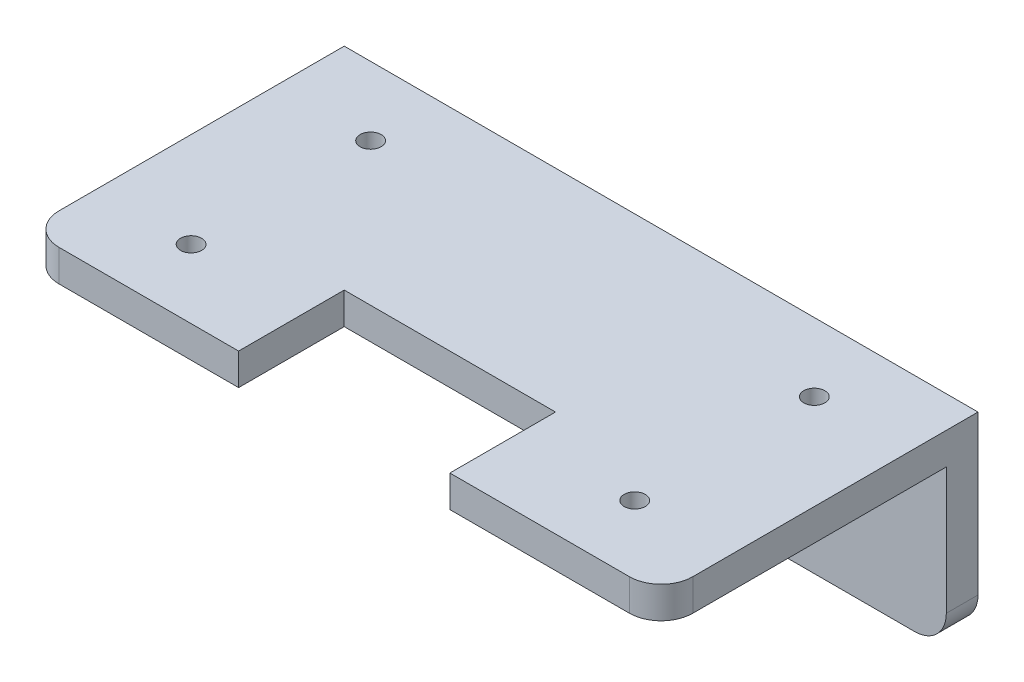
SolidWorks part; units mm, degrees
ref_plane "Front Plane" through (0, 0, 0) normal (0, 0, 1) x (1, 0, 0)
ref_plane "Top Plane" through (0, 0, 0) normal (0, 1, 0) x (1, 0, 0)
ref_plane "Right Plane" through (0, 0, 0) normal (1, 0, 0) x (0, 0, -1)
sketch "Sketch1" plane through (0, 0, 0) normal (0, 0, 1) x (1, 0, 0)
  line L0 (80, 160) -> (-80, 160) construction
  line L1 (-30, 160) -> (30, 160)
  line L2 (-30, 160) -> (-30, 157)
  line L3 (-30, 157) -> (30, 157)
  line L4 (30, 160) -> (30, 157)
  line L5 (0, 164) -> (0, 138.3232) construction
  line L6 (-4.5, 164) -> (4.5, 164) construction
  dimension "D1" = 30
  dimension "D2" = 60
  dimension "D3" = 3
extrude "Boss-Extrude1" add sketch "Sketch1" along normal blind 30
sketch "Sketch2" plane through (0, 157, 0) normal (0, -1, 0) x (1, 0, 0)
  line L0 (30, 30) -> (30, 0) construction
  line L1 (-30, 0) -> (30, 0)
  line L2 (-30, 0) -> (-30, 3)
  line L3 (-30, 3) -> (30, 3)
  line L4 (30, 0) -> (30, 3)
  dimension "D1" = 3
extrude "Boss-Extrude2" add sketch "Sketch2" along normal blind 15
sketch "Sketch3" plane through (0, 157, 0) normal (0, -1, 0) x (1, 0, 0)
  line L0 (-30, 30) -> (30, 30) construction
  line L1 (-10, 30) -> (10, 30)
  line L2 (-10, 30) -> (-10, 20)
  line L3 (-10, 20) -> (10, 20)
  line L4 (10, 30) -> (10, 20)
  line L5 (30, 30) -> (30, 3) construction
  line L6 (-30, 30) -> (-30, 3) construction
  dimension "D1" = 20
  dimension "D2" = 20
  dimension "D3" = 10
extrude "Cut-Extrude1" cut sketch "Sketch3" against normal through all
fillet "Fillet1" radius 3 4 edges at (-30, 142, 1.5) (30, 142, 1.5) (30, 158.5, 30) (-30, 158.5, 30)
sketch "Sketch4" plane through (0, 160, 0) normal (0, 1, 0) x (1, 0, 0)
  circle A0 centre (-21, -23.5) radius 1
  circle A1 centre (-21, -6.5) radius 1
  circle A2 centre (21, -6.5) radius 1
  circle A3 centre (21, -23.5) radius 1
extrude "Cut-Extrude2" cut sketch "Sketch4" against normal blind 10
